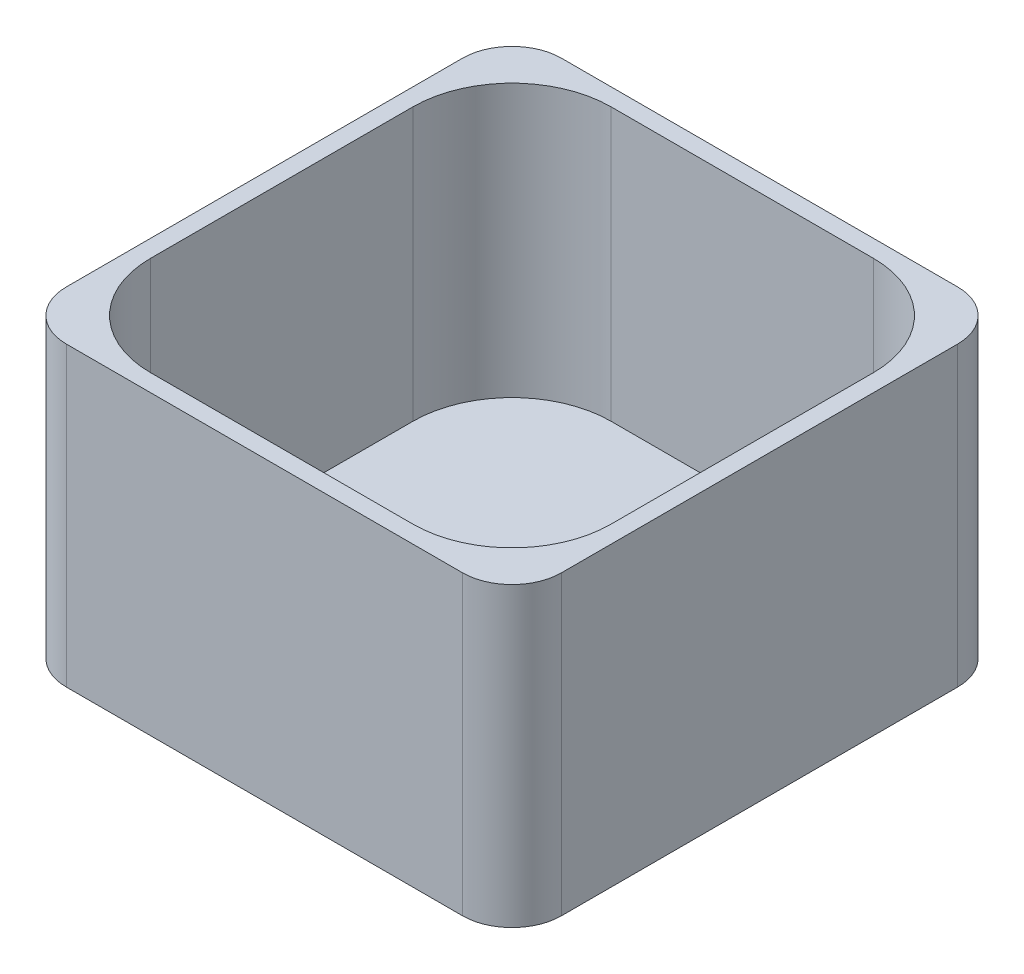
SolidWorks part; units mm, degrees
ref_plane "Front Plane" through (0, 0, 0) normal (0, 0, 1) x (1, 0, 0)
ref_plane "Top Plane" through (0, 0, 0) normal (0, 1, 0) x (1, 0, 0)
ref_plane "Right Plane" through (0, 0, 0) normal (1, 0, 0) x (0, 0, -1)
sketch "Sketch1" plane through (0, 0, 0) normal (0, 1, 0) x (1, 0, 0)
  line L1 (-50, -50) -> (50, -50)
  line L2 (-50, -50) -> (-50, 50)
  line L3 (-50, 50) -> (50, 50)
  line L4 (50, -50) -> (50, 50)
  line L5 (-50, -50) -> (50, 50) construction
  line L6 (-50, 50) -> (50, -50) construction
  point P0 (0, 0)
  dimension "D1" = 100
  dimension "D2" = 100
extrude "Boss-Extrude1" add sketch "Sketch1" along normal blind 60
sketch "Sketch2" plane through (0, 60, 0) normal (0, 1, 0) x (1, 0, 0)
  line L1 (-46.5, -46.5) -> (46.5, -46.5)
  line L2 (-46.5, -46.5) -> (-46.5, 46.5)
  line L3 (-46.5, 46.5) -> (46.5, 46.5)
  line L4 (46.5, -46.5) -> (46.5, 46.5)
  line L5 (-46.5, -46.5) -> (46.5, 46.5) construction
  line L6 (-46.5, 46.5) -> (46.5, -46.5) construction
  point P0 (0, 0)
  dimension "D1" = 93
  dimension "D2" = 93
extrude "Cut-Extrude1" cut sketch "Sketch2" against normal blind 55
sketch "Sketch3" plane through (0, 5, 0) normal (0, 1, 0) x (1, 0, 0)
  circle A0 centre (0, 0) radius 20
  dimension "D1" = 40
extrude "Cut-Extrude2" cut sketch "Sketch3" against normal blind 66
fillet "Fillet1" radius 20 4 edges at (-46.5, 32.5, 46.5) (-46.5, 32.5, -46.5) (46.5, 32.5, -46.5) (46.5, 32.5, 46.5)
fillet "Fillet2" radius 10 4 edges at (50, 30, -50) (-50, 30, -50) (-50, 30, 50) (50, 30, 50)
